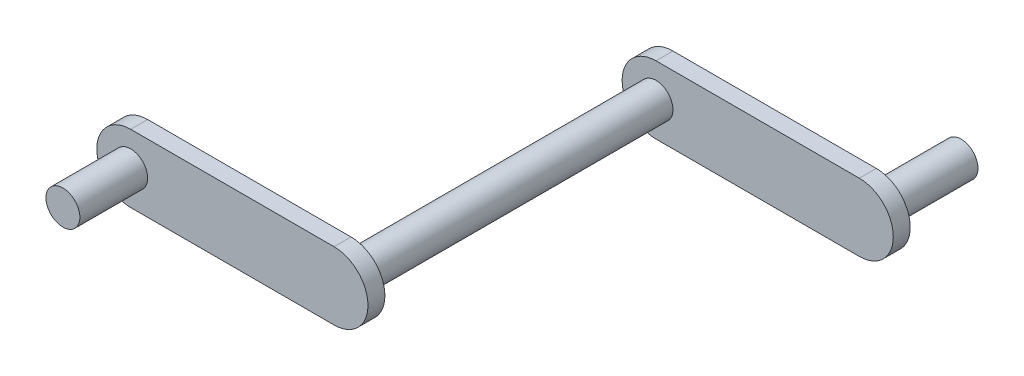
SolidWorks part; units mm, degrees
material "Chrome Stainless Steel"
ref_plane "Front Plane" through (0, 0, 0) normal (0, 0, 1) x (1, 0, 0)
ref_plane "Top Plane" through (0, 0, 0) normal (0, 1, 0) x (1, 0, 0)
ref_plane "Right Plane" through (0, 0, 0) normal (1, 0, 0) x (0, 0, -1)
sketch "Sketch1" plane through (0, 0, 0) normal (0, 0, 1) x (1, 0, 0)
  line L0 (-139.4896, 0.1574) -> (49860.5104, 0.1574) construction
  line L1 (0, 0) -> (0, 71.3201) construction
  line L2 (-190.5, 63.6574) -> (190.5, 63.6574)
  line L3 (-190.5, -63.3426) -> (190.5, -63.3426)
  arc A0 (-190.5, 63.6574) -> (-190.5, -63.3426) centre (-190.5, 0.1574) ccw
  arc A1 (190.5, -63.3426) -> (190.5, 63.6574) centre (190.5, 0.1574) ccw
  circle A3 centre (190.5, 0.1574) radius 31.75
  dimension "D2" = 63.5
  dimension "D3" = 63.5
  dimension "D1" = 381
extrude "Boss-Extrude1" add sketch "Sketch1" along normal mid plane 31.75
sketch "Sketch2" plane through (0, 0, 15.875) normal (0, 0, 1) x (1, 0, 0)
  circle A0 centre (-190.5, 0.1574) radius 31.75
  dimension "D1" = 63.5
extrude "Boss-Extrude2" add sketch "Sketch2" along normal blind 571.5
sketch "Sketch4" plane through (0, 0, 15.875) normal (0, 0, 1) x (1, 0, 0)
  circle A1 centre (190.5, 0.1574) radius 31.75
  circle A3 centre (190.5, 0.1574) radius 31.75
  dimension "D2" = 0
extrude "Boss-Extrude3" add sketch "Sketch4" against normal blind 190.5
sketch "Sketch6" plane through (0, 0, 587.375) normal (0, 0, 1) x (1, 0, 0)
  line L0 (-381, -199.3972) -> (-381, 244.1739) construction
  line L1 (-571.5, 63.6574) -> (-190.5, 63.6574)
  line L2 (-571.5, -63.3426) -> (-190.5, -63.3426)
  arc A0 (-571.5, 63.6574) -> (-571.5, -63.3426) centre (-571.5, 0.1574) ccw
  arc A1 (-190.5, -63.3426) -> (-190.5, 63.6574) centre (-190.5, 0.1574) ccw
  circle A2 centre (-190.5, 0.1574) radius 31.75
  dimension "D2" = 63.5
  dimension "D3" = 63.5
  dimension "D1" = 381
extrude "Boss-Extrude4" add sketch "Sketch6" along normal blind 31.75 contours L1 A1 L2 A0
sketch "Sketch7" plane through (0, 0, 619.125) normal (0, 0, 1) x (1, 0, 0)
  circle A0 centre (-571.5, 0.1574) radius 31.75
  arc A1 (-571.5, 63.6574) -> (-571.5, -63.3426) centre (-571.5, 0.1574) ccw construction
  dimension "D1" = 63.5
extrude "Boss-Extrude5" add sketch "Sketch7" along normal blind 127 contours A0
